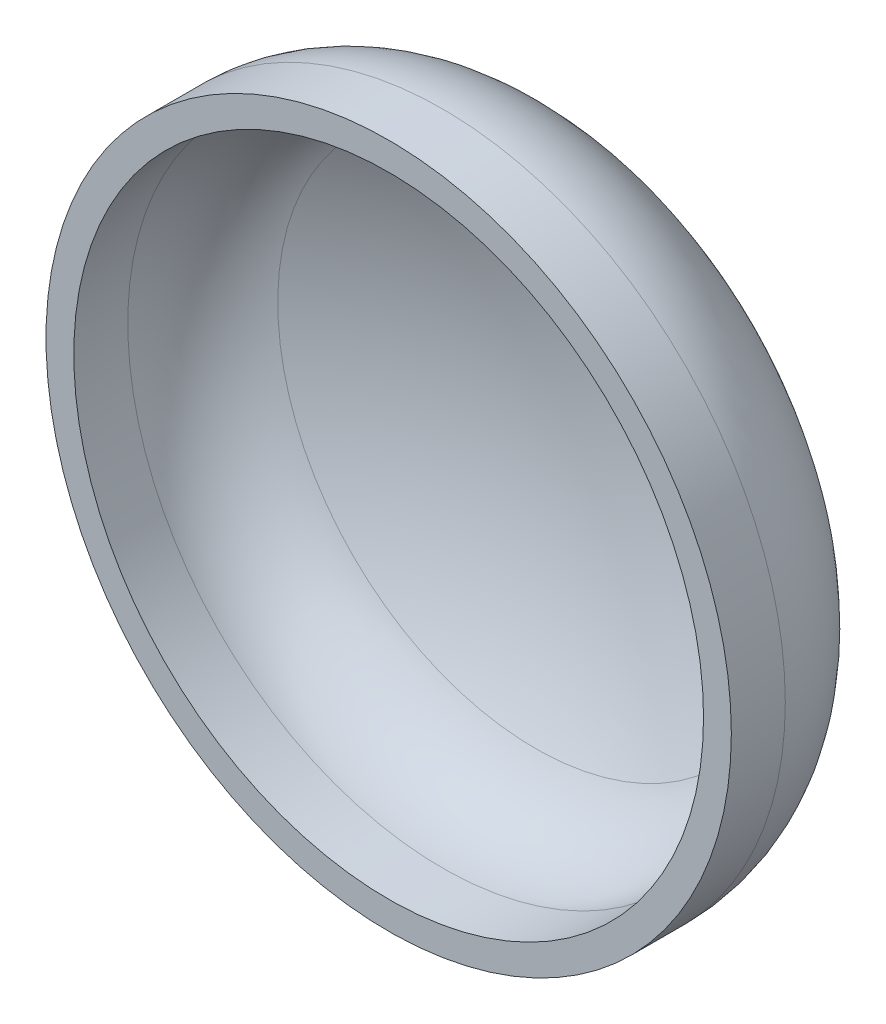
SolidWorks part; units mm, degrees
ref_plane "Front Plane" through (0, 0, 0) normal (0, 0, 1) x (1, 0, 0)
ref_plane "Top Plane" through (0, 0, 0) normal (0, 1, 0) x (1, 0, 0)
ref_plane "Right Plane" through (0, 0, 0) normal (1, 0, 0) x (0, 0, -1)
sketch "Sketch1" plane through (0, 0, 0) normal (1, 0, 0) x (0, 0, -1)
  line L0 (0, 0) -> (222.2643, 0) construction
  line L1 (0, 254) -> (40, 254)
  line L2 (0, 233.4) -> (40, 233.4)
  line L3 (0, 254) -> (0, 233.4)
  line L4 (154.1254, 0) -> (174.7254, 0)
  arc A0 (40, 254) -> (127.1878, 200.2639) centre (40, 156.4) cw
  arc A1 (127.1878, 200.2639) -> (174.7254, 0) centre (-270.8746, 0) cw
  arc A2 (40, 233.4) -> (108.7855, 191.0057) centre (40, 156.4) cw
  arc A3 (108.7855, 191.0057) -> (154.1254, 0) centre (-270.8746, 0) cw
  arc A4 (108.7855, 191.0057) -> (154.1254, 0) centre (-270.8746, 0) cw construction
  dimension "D2" = 77
  dimension "D3" = 20.6
  dimension "D5" = 425
  dimension "D1" = 40
  dimension "D4" = 508
revolve "Revolve1" add sketch "Sketch1" angle 360 about L0
